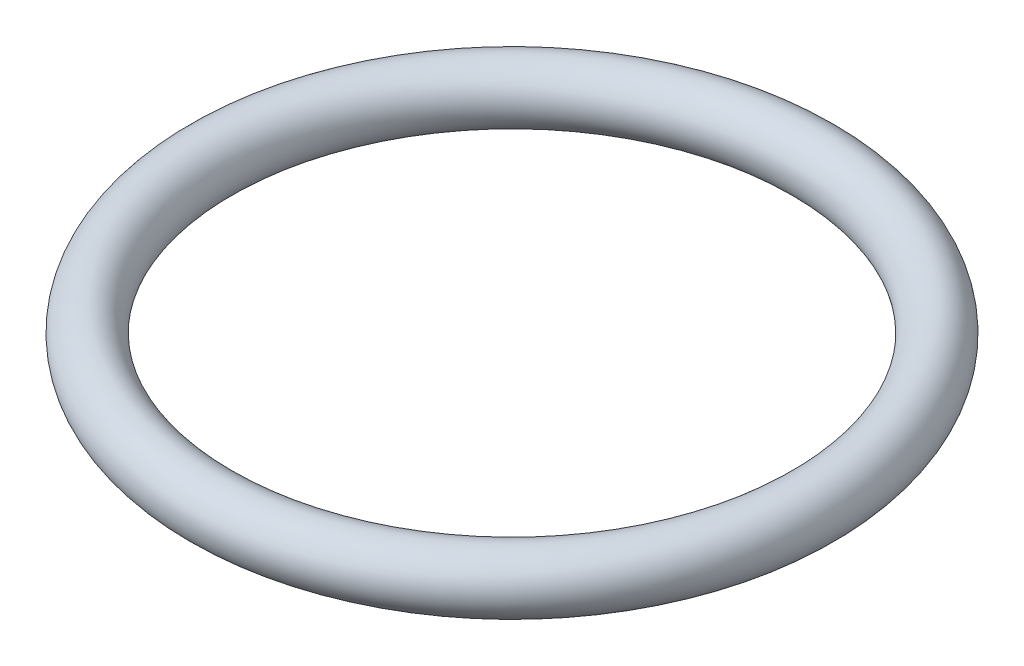
SolidWorks part; units mm, degrees
material "NBR"
ref_plane "Ön Düzlem" through (0, 0, 0) normal (0, 0, 1) x (1, 0, 0)
ref_plane "Üst Düzlem" through (0, 0, 0) normal (0, 1, 0) x (1, 0, 0)
ref_plane "Sağ Düzlem" through (0, 0, 0) normal (1, 0, 0) x (0, 0, -1)
sketch "Çizim1" plane through (0, 0, 0) normal (0, 0, 1) x (1, 0, 0)
  line L3 (0, 0) -> (0, -9.2489)
  circle A2 centre (-18.225, 0) radius 1.765
revolve "Döndür1" add sketch "Çizim1" angle 360 about L3
sketch "Çizim3" plane through (0, 0, 0) normal (0, 1, 0) x (1, 0, 0)
  circle A0 centre (0, 0) radius 32.2221
sketch "Çizim4" plane through (0, 0, 0) normal (0, 0, 1) x (1, 0, 0)
  line L0 (-21.8631, 1.765) -> (21.9391, 1.765)
  line L1 (18.225, 1.765) -> (-18.225, 1.765) construction
